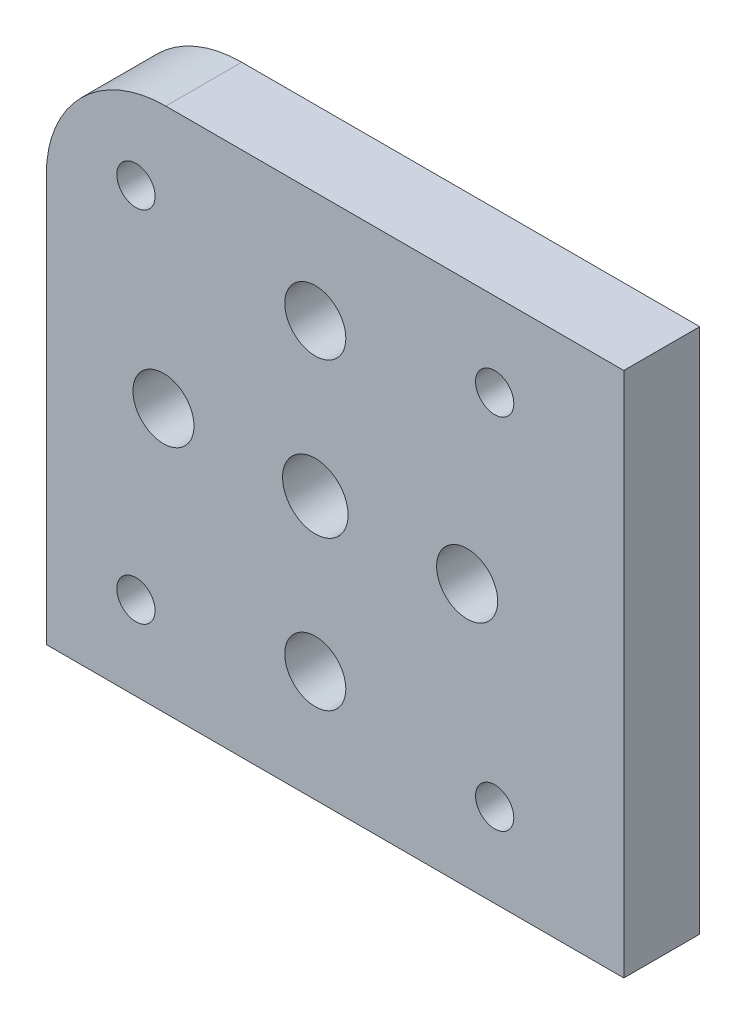
SolidWorks part; units mm, degrees
ref_plane "Front Plane" through (0, 0, 0) normal (0, 0, 1) x (1, 0, 0)
ref_plane "Top Plane" through (0, 0, 0) normal (0, 1, 0) x (1, 0, 0)
ref_plane "Right Plane" through (0, 0, 0) normal (1, 0, 0) x (0, 0, -1)
sketch "Sketch1" plane through (0, 0, 0) normal (0, 0, 1) x (1, 0, 0)
  line L0 (22.5, -9.3) -> (22.5, -34.7) construction
  line L1 (0, 0) -> (48.3, 0)
  line L2 (0, 0) -> (0, -44)
  line L3 (0, -44) -> (48.3, -44)
  line L4 (48.3, 0) -> (48.3, -44)
  line L5 (9.8, -22) -> (35.2, -22) construction
  circle A0 centre (7.5, -37) radius 1.6
  circle A16 centre (22.5, -9.3) radius 2.5527
  circle A17 centre (35.2, -22) radius 2.5527
  circle A18 centre (9.8, -22) radius 2.5527
  circle A19 centre (22.5, -34.7) radius 2.5527
  circle A20 centre (37.5, -37) radius 1.6
  circle A21 centre (37.5, -7) radius 1.6
  circle A22 centre (7.5, -7) radius 1.6
  circle A23 centre (22.5, -22) radius 2.7406
  point P12 (48.3, -22)
  point P47 (22.5, -22)
  dimension "D3" = 3.2
  dimension "D10" = 5.1054
  dimension "D1" = 48.3
  dimension "D2" = 44
  dimension "D4" = 7.5
  dimension "D5" = 7
  dimension "D11" = 25.4
  dimension "D8" = 30
  dimension "D9" = 30
  dimension "D12" = 22.5
  dimension "D13" = 25.8
  dimension "D14" = 22
  dimension "D15" = 22
  dimension "D6" = 2
  dimension "D7" = 2
extrude "Boss-Extrude1" add sketch "Sketch1" along normal blind 6.35
hole_wizard "1/4-20 Tapped Hole1" positions "3DSketch1" profile "Sketch2" tap size "1/4-20" standard "ANSI Inch" end condition through all
sketch3d "3DSketch1"
  circle A0 centre (22.5, -9.3, 6.35) radius 2.5527 construction
  circle A1 centre (9.8, -22, 6.35) radius 2.5527 construction
  circle A2 centre (22.5, -34.7, 6.35) radius 2.5527 construction
  circle A3 centre (35.2, -22, 6.35) radius 2.5527 construction
  point P0 (22.5, -9.3, 6.35)
  point P2 (35.2, -22, 6.35)
  point P4 (9.8, -22, 6.35)
  point P6 (22.5, -34.7, 6.35)
  point P13 (22.5, -9.3, 8.9027)
  point P20 (9.8, -22, 8.9027)
  point P24 (22.5, -34.7, 8.9027)
  point P28 (35.2, -22, 8.9027)
sketch "Sketch2" plane through (22.5, -9.3, 6.35) normal (1, 0, 0) x (0, -1, 0)
  line L0 (0, 0) -> (0, 6.35)
  line L1 (0, 6.35) -> (2.5527, 6.35)
  line L2 (2.5527, 6.35) -> (2.5527, 0)
  line L5 (2.5527, 0) -> (0, 0)
  line L11 (0, -6.35) -> (0, 107.95) construction
  dimension "Thru Tap Drill Dia." = 5.1054
  dimension "Thru Tap Drill Depth" = 6.35
cosmetic thread "Hole Thread1" parameters "D2"=6.35
cosmetic thread "Hole Thread2" parameters "D2"=6.35
cosmetic thread "Hole Thread3" parameters "D2"=6.35
cosmetic thread "Hole Thread4" parameters "D2"=6.35
sketch "Sketch4" plane through (0, 0, 6.35) normal (0, 0, 1) x (1, 0, 0)
  line L0 (22.5, -22) -> (0, 0) construction
fillet "Fillet1" radius 10 1 edges at (0, 0, 3.175)
equation "\"D4@Sketch1\"=(\"D1@Sketch1\"-\"D9@Sketch1\")/2-1.65"
